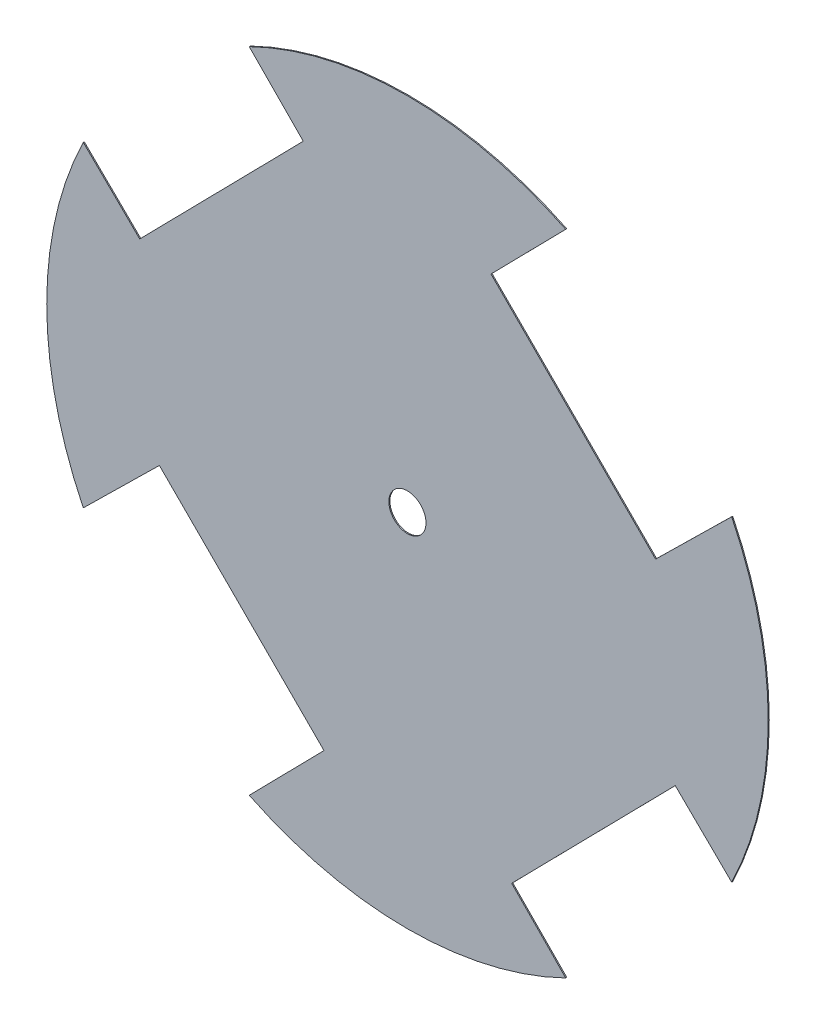
SolidWorks part; units mm, degrees
ref_plane "Front Plane" through (0, 0, 0) normal (0, 0, 1) x (1, 0, 0)
ref_plane "Top Plane" through (0, 0, 0) normal (0, 1, 0) x (1, 0, 0)
ref_plane "Right Plane" through (0, 0, 0) normal (1, 0, 0) x (0, 0, -1)
sketch "Sketch2" plane through (0, 0, 0) normal (0, 0, 1) x (1, 0, 0)
  line L0 (767.9479, -1572.6258) -> (505.9065, -1305.9815)
  line L1 (505.9065, -1305.9815) -> (1299.2113, -498.7421)
  line L2 (1299.2113, -498.7421) -> (1572.8835, -767.6902)
  line L3 (1572.8835, 767.6902) -> (1203.8296, 405.0068)
  line L4 (1203.8296, 405.0068) -> (405.2646, 1203.5718)
  line L5 (405.2646, 1203.5718) -> (767.9479, 1572.6258)
  line L6 (-767.4324, 1572.6258) -> (-505.391, 1305.9815)
  line L7 (-505.391, 1305.9815) -> (-1298.6958, 498.7421)
  line L8 (-1298.6958, 498.7421) -> (-1572.368, 767.6902)
  line L9 (-1572.368, -767.6902) -> (-1203.3141, -405.0068)
  line L10 (-1203.3141, -405.0068) -> (-404.7491, -1203.5718)
  line L11 (-404.7491, -1203.5718) -> (-767.4324, -1572.6258)
  arc A0 (-767.4324, -1572.6258) -> (767.9479, -1572.6258) centre (0.2578, 0) ccw
  arc A1 (1572.8835, -767.6902) -> (1572.8835, 767.6902) centre (0.2578, 0) ccw
  arc A2 (767.9479, 1572.6258) -> (-767.4324, 1572.6258) centre (0.2578, 0) ccw
  arc A3 (-1572.368, 767.6902) -> (-1572.368, -767.6902) centre (0.2578, 0) ccw
  circle A4 centre (-1090, 0) radius 90
  circle A5 centre (1090, 0) radius 90
  dimension "D1" = 2
extrude "Boss-Extrude1" add sketch "Sketch2" along normal blind 5 contours L0 L1 L2 A1 L3 L4 L5 A2 L6 L7 L8 A3 L9 L10 L11 A0
sketch "Sketch3" plane through (0, 0, 0) normal (0, 0, 1) x (1, 0, 0)
  circle A2 centre (0, 0) radius 90
extrude "Cut-Extrude3" cut sketch "Sketch3" along normal blind 10
